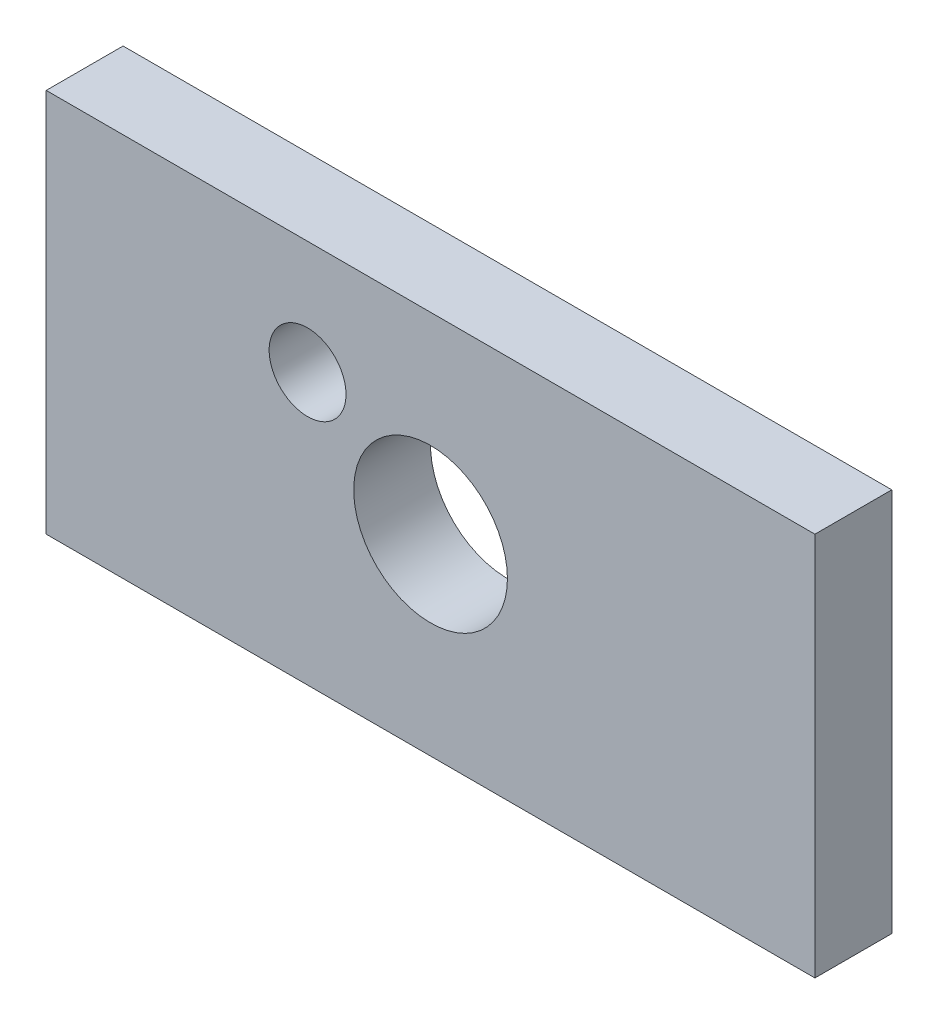
SolidWorks part; units mm, degrees
ref_plane "Front Plane" through (0, 0, 0) normal (0, 0, 1) x (1, 0, 0)
ref_plane "Top Plane" through (0, 0, 0) normal (0, 1, 0) x (1, 0, 0)
ref_plane "Right Plane" through (0, 0, 0) normal (1, 0, 0) x (0, 0, -1)
sketch "Sketch1" plane through (0, 0, 0) normal (0, 0, 1) x (1, 0, 0)
  line L1 (0, 0) -> (100, 0)
  line L2 (0, 0) -> (0, 50)
  line L3 (0, 50) -> (100, 50)
  line L4 (100, 0) -> (100, 50)
  circle A0 centre (50, 25) radius 10
  circle A1 centre (34, 35.247) radius 5
  dimension "D3" = 20
  dimension "D4" = 50
  dimension "D6" = 10
  dimension "D8" = 19
  dimension "D1" = 100
  dimension "D2" = 50
  dimension "D5" = 25
  dimension "D7" = 34
extrude "Boss-Extrude1" add sketch "Sketch1" along normal blind 10
